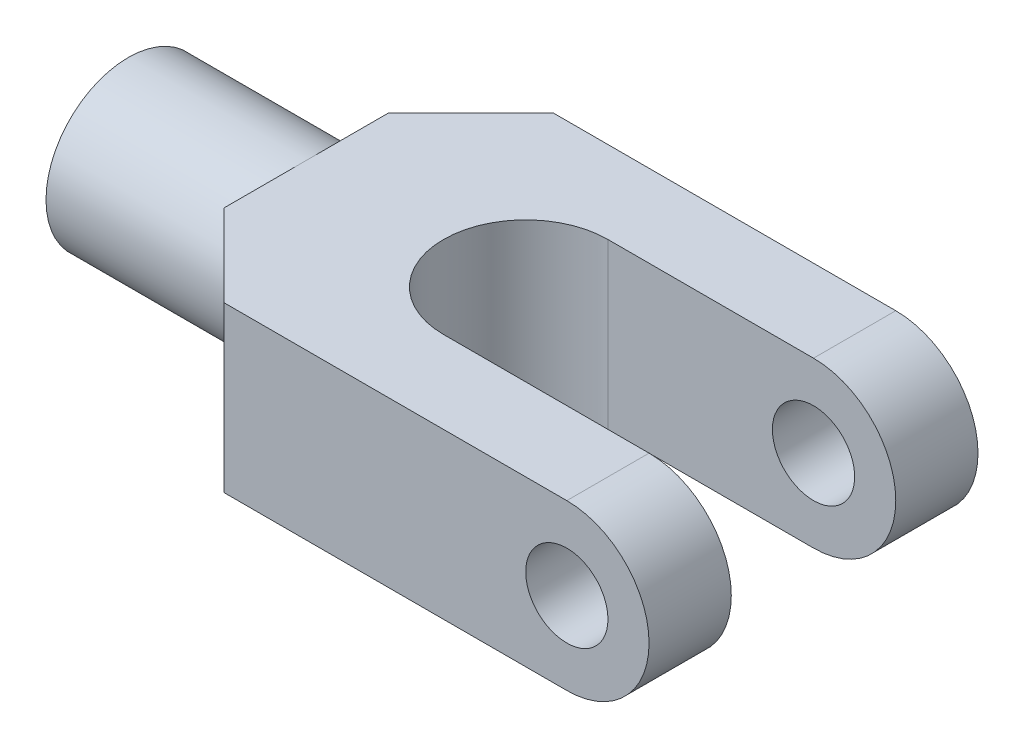
SolidWorks part; units mm, degrees
material "Plain Carbon Steel"
ref_plane "Front Plane" through (0, 0, 0) normal (0, 0, 1) x (1, 0, 0)
ref_plane "Top Plane" through (0, 0, 0) normal (0, 1, 0) x (1, 0, 0)
ref_plane "Right Plane" through (0, 0, 0) normal (1, 0, 0) x (0, 0, -1)
sketch "Sketch1" plane through (0, 0, 0) normal (0, 0, 1) x (1, 0, 0)
  line L0 (0, 0) -> (-7902.1702, 0) construction
  line L1 (0, 0) -> (0, -7902.1702) construction
  line L2 (0, -6) -> (-31, -6)
  line L3 (-31, -6) -> (-31, 6)
  line L4 (-31, 6) -> (0, 6)
  circle A0 centre (0, 0) radius 3
  arc A1 (0, -6) -> (0, 6) centre (0, 0) ccw
  point P11 (-31, 0)
  dimension "D1" = 6
  dimension "D2" = 6
  dimension "D3" = 31
extrude "Boss-Extrude1" add sketch "Sketch1" along normal mid plane 24
sketch "Sketch2" plane through (0, 0, 0) normal (0, 1, 0) x (1, 0, 0)
  line L0 (0, 0) -> (-50000, 0) construction
  line L1 (-15, 6) -> (6, 6)
  line L2 (6, -12) -> (6, 12) construction
  line L3 (6, 6) -> (6, -6)
  line L4 (6, -6) -> (-15, -6)
  line L5 (-31, 6) -> (-25, 12)
  line L6 (-31, -12) -> (-31, 12) construction
  line L7 (0, 12) -> (-31, 12) construction
  line L8 (-25, 12) -> (-31, 12)
  line L9 (-31, 12) -> (-31, 6)
  line L10 (-31, -12) -> (-31, -6)
  line L11 (-25, -12) -> (-31, -12)
  line L12 (-31, -6) -> (-25, -12)
  arc A0 (-15, -6) -> (-15, 6) centre (-15, 0) cw
  point P7 (6, 0)
  point P11 (-21, 0)
  dimension "D1" = 6
  dimension "D2" = 27
  dimension "D3" = 6
  dimension "D4" = 6
extrude "Cut-Extrude1" cut sketch "Sketch2" against normal through all both and the other way through all
sketch "Sketch3" plane through (-31, 0, 0) normal (-1, 0, 0) x (0, 0, 1)
  circle A0 centre (0, 0) radius 6
  circle A1 centre (0, 0) radius 3
  dimension "D1" = 12
  dimension "D2" = 6
extrude "Boss-Extrude2" add sketch "Sketch3" along normal blind 13 contours A0 A1
cosmetic thread "Cosmetic Thread1" parameters "D2"=8
